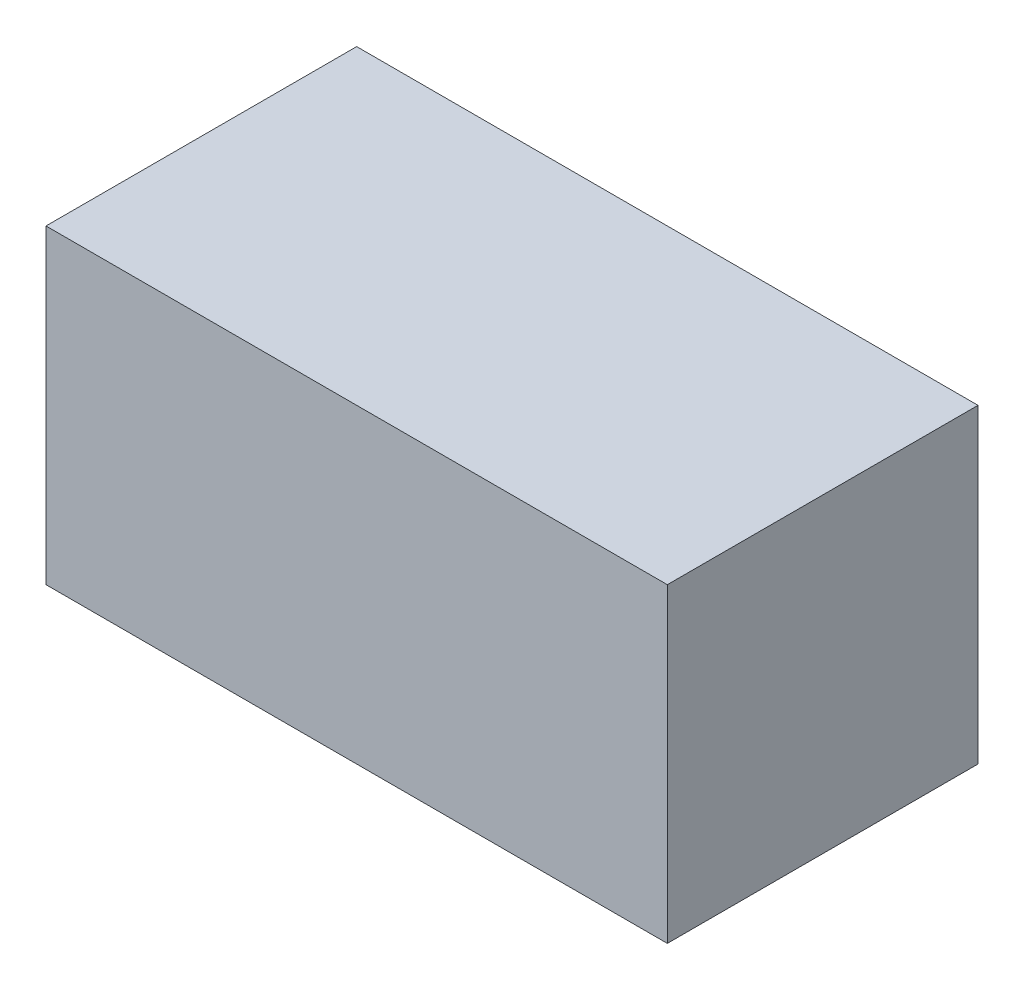
SolidWorks part; units mm, degrees
ref_plane "Front Plane" through (0, 0, 0) normal (1, 0, 0) x (0, 1, 0)
ref_plane "Top Plane" through (0, 0, 0) normal (0, 0, 1) x (0, 1, 0)
ref_plane "Right Plane" through (0, 0, 0) normal (0, 1, 0) x (-1, 0, 0)
sketch "Sketch1" plane through (0, 0, 0) normal (1, 0, 0) x (0, 1, 0)
  line L1 (0, 0) -> (1000, 0)
  line L2 (0, 0) -> (0, -1000)
  line L3 (0, -1000) -> (1000, -1000)
  line L4 (1000, 0) -> (1000, -1000)
  dimension "D1" = 1000
  dimension "D2" = 1000
extrude "Boss-Extrude1" add sketch "Sketch1" along normal blind 2000
